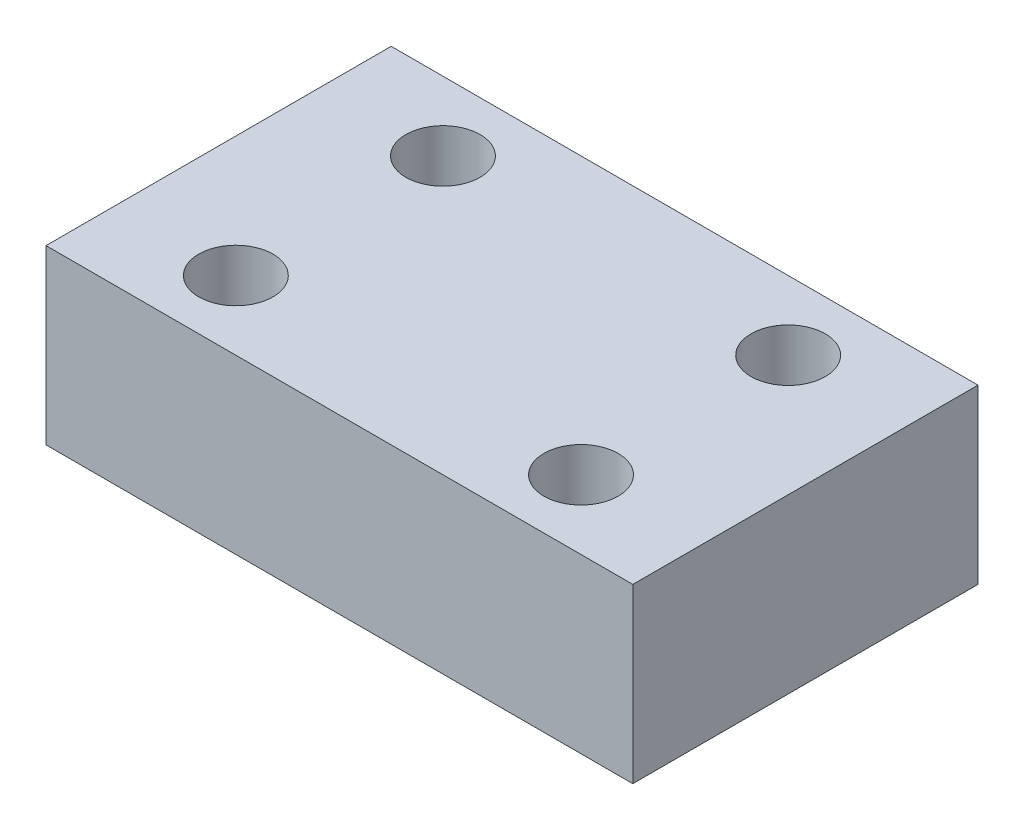
SolidWorks part; units mm, degrees
material "6061-T6 (SS)"
ref_plane "Front Plane" through (0, 0, 0) normal (0, 0, 1) x (1, 0, 0)
ref_plane "Top Plane" through (0, 0, 0) normal (0, 1, 0) x (1, 0, 0)
ref_plane "Right Plane" through (0, 0, 0) normal (1, 0, 0) x (0, 0, -1)
sketch "Sketch1" plane through (0, 0, 0) normal (0, 0, 1) x (1, 0, 0)
  line L0 (-70, 30) -> (-70, 10) construction
  line L1 (-80, 40) -> (80, 40)
  line L2 (-80, 40) -> (-80, 0)
  line L3 (-80, 0) -> (80, 0)
  line L4 (80, 40) -> (80, 0)
  line L9 (37, 23) -> (43, 23) construction
  line L10 (37, 23) -> (37, 17) construction
  line L11 (37, 17) -> (43, 17) construction
  line L12 (43, 23) -> (43, 17) construction
  line L13 (0, 0) -> (0, 40) construction
  line L14 (37, 20) -> (43, 20) construction
  line L15 (40, 17) -> (40, 23) construction
  line L16 (22.5, 40) -> (22.5, 22.95)
  line L17 (22.5, 40) -> (57.5, 40) construction
  line L18 (22.5, 40) -> (22.5, 23) construction
  line L19 (22.5, 23) -> (57.5, 23) construction
  line L20 (57.5, 40) -> (57.5, 23) construction
  line L21 (22.5, 22.95) -> (37, 22.95)
  line L22 (37, 22.95) -> (37, 17)
  line L23 (37, 17) -> (43, 17)
  line L24 (43, 17) -> (43, 22.95)
  line L25 (43, 22.95) -> (57.5, 22.95)
  line L26 (57.5, 22.95) -> (57.5, 40)
  circle A0 centre (-70, 30) radius 2.5 construction
  circle A1 centre (-70, 10) radius 2.5 construction
  circle A2 centre (70, 10) radius 2.5 construction
  circle A3 centre (70, 30) radius 2.5 construction
  point P10 (0, 0)
  point P15 (80, 20)
  point P31 (40, 23)
  dimension "D8" = 5
  dimension "D10" = 10
  dimension "D2" = 160
  dimension "D3" = 40
  dimension "D4" = 40
  dimension "D5" = 35
  dimension "D6" = 6
  dimension "D7" = 20
  dimension "D9" = 10
  dimension "D11" = 0.05
extrude "Boss-Extrude1" [suppressed] add sketch "Sketch1" against normal blind 20
sketch "Sketch4" [suppressed] plane through (0, 0, 0) normal (0, -1, 0) x (1, 0, 0)
  line L0 (-60, -10) -> (60, -10) construction
  line L2 (-80, 0) -> (80, 0)
  line L3 (-80, 0) -> (-80, -20)
  line L4 (-80, -20) -> (80, -20)
  line L5 (80, 0) -> (80, -20)
  circle A0 centre (0, -10) radius 2.5 construction
  circle A1 centre (60, -10) radius 2.5 construction
  circle A2 centre (-60, -10) radius 2.5 construction
  point P6 (0, -10)
  point P14 (80, -10)
  dimension "D1" = 5
  dimension "D2" = 120
sketch "Sketch8" [suppressed] plane through (0, 22.95, 0) normal (0, 1, 0) x (1, 0, 0)
  line L8 (37, 0) -> (22.5, 0) construction
  line L9 (22.5, 0) -> (22.5, 20) construction
  line L10 (22.5, 20) -> (37, 20) construction
  line L11 (37, 20) -> (37, 0) construction
  line L12 (57.5, 0) -> (43, 0) construction
  line L13 (43, 0) -> (43, 20) construction
  line L14 (43, 20) -> (57.5, 20) construction
  line L15 (57.5, 20) -> (57.5, 0) construction
  line L16 (30, 5) -> (50, 5) construction
  line L17 (37, 20) -> (43, 20)
  line L18 (37, 20) -> (37, 0) construction
  line L19 (37, 20) -> (37, 0) construction
  line L20 (30, 5) -> (30, 15) construction
  line L21 (30, 15) -> (50, 15) construction
  line L22 (50, 15) -> (50, 5) construction
  circle A0 centre (50, 5) radius 2 construction
  circle A1 centre (30, 5) radius 2 construction
  circle A2 centre (30, 15) radius 2 construction
  circle A3 centre (50, 15) radius 2 construction
  point P4 (40, 5)
  point P5 (40, 20)
  point P17 (50, 10)
  point P18 (43, 10)
  dimension "D1" = 4
  dimension "D2" = 20
  dimension "D3" = 10
hole_wizard "Tap Drill for M4x0.7 Tap1" [suppressed] positions "3DSketch3" profile "Sketch9" hole size "M4x0.7" standard "ANSI Metric"
sketch3d "3DSketch3" [suppressed]
  point P10 (30, 22.95, -5)
  point P12 (50, 22.95, -5)
  point P19 (30, 22.95, -15)
  point P21 (50, 22.95, -15)
sketch "Sketch9" plane through (30, 22.95, -5) normal (1, 0, 0) x (0, 0, 1)
  line L0 (0, 0) -> (0, 5.9914)
  line L1 (0, 5.9914) -> (1.65, 5)
  line L2 (1.65, 5) -> (1.65, 0)
  line L5 (1.65, 0) -> (0, 0)
  line L10 (0, 5.9914) -> (-1.65, 5) construction
  line L11 (0, -6.35) -> (0, 107.95) construction
  dimension "Hole Dia." = 3.3
  dimension "Hole Depth" = 5
  dimension "Drill Angle" = 118
hole_wizard "Tap Drill for M5x0.8 Tap3" [suppressed] positions "3DSketch4" profile "Sketch10" hole size "M5x0.8" standard "ANSI Metric"
sketch3d "3DSketch4" [suppressed]
  point P0 (-70, 30, 0)
  point P2 (-70, 10, 0)
  point P4 (70, 10, 0)
  point P6 (70, 30, 0)
sketch "Sketch10" plane through (-70, 30, 0) normal (1, 0, 0) x (0, -1, 0)
  line L0 (0, 0) -> (0, 20)
  line L1 (0, 20) -> (2.1, 20)
  line L2 (2.1, 20) -> (2.1, 0)
  line L5 (2.1, 0) -> (0, 0)
  line L11 (0, -6.35) -> (0, 107.95) construction
  dimension "Thru Hole Dia." = 4.2
  dimension "Thru Hole Depth" = 20
hole_wizard "Tap Drill for M5x0.8 Tap2" [suppressed] positions "3DSketch2" profile "Sketch5" hole size "M5x0.8" standard "ANSI Metric"
sketch3d "3DSketch2" [suppressed]
  point P0 (-60, 0, -10)
  point P2 (0, 0, -10)
  point P4 (60, 0, -10)
sketch "Sketch5" plane through (-60, 0, -10) normal (1, 0, 0) x (0, 0, -1)
  line L0 (0, 0) -> (0, 8.2618)
  line L1 (0, 8.2618) -> (2.1, 7)
  line L2 (2.1, 7) -> (2.1, 0)
  line L5 (2.1, 0) -> (0, 0)
  line L10 (0, 8.2618) -> (-2.1, 7) construction
  line L11 (0, -6.35) -> (0, 107.95) construction
  dimension "Hole Dia." = 4.2
  dimension "Hole Depth" = 7
  dimension "Drill Angle" = 118
fillet "Fillet1" [suppressed] radius 1
ref_plane "Plane1" [suppressed] through (0, 0, -10) normal (0, 0, -1) x (-1, 0, 0)
sketch "Sketch12" plane through (0, 0, 0) normal (0, 1, 0) x (1, 0, 0)
  line L1 (-17, 10) -> (17, 10)
  line L2 (-17, 10) -> (-17, -10)
  line L3 (-17, -10) -> (17, -10)
  line L4 (17, 10) -> (17, -10)
  line L5 (-10, 6) -> (10, 6) construction
  line L6 (-10, 6) -> (-10, -6) construction
  line L7 (-10, -6) -> (10, -6) construction
  line L8 (10, 6) -> (10, -6) construction
  circle A0 centre (-10, 6) radius 2 construction
  circle A1 centre (-10, -6) radius 2 construction
  circle A2 centre (10, -6) radius 2 construction
  circle A3 centre (10, 6) radius 2 construction
  point P8 (0, 6)
  point P9 (0, 10)
  point P11 (-10, 0)
  point P12 (-17, 0)
  dimension "D3" = 4
  dimension "D1" = 34
  dimension "D2" = 20
  dimension "D4" = 12
  dimension "D5" = 20
extrude "Boss-Extrude2" add sketch "Sketch12" against normal blind 10
hole_wizard "M4 Clearance Hole1" positions "3DSketch5" profile "Sketch13" hole size "M4" standard "ANSI Metric" end condition through all
sketch3d "3DSketch5"
  point P0 (-10, 0, -6)
  point P2 (-10, 0, 6)
  point P4 (10, 0, 6)
  point P7 (10, 0, -6)
sketch "Sketch13" plane through (-10, 0, -6) normal (1, 0, 0) x (0, 0, 1)
  line L0 (0, 0) -> (0, 10)
  line L1 (0, 10) -> (2.15, 10)
  line L2 (2.15, 10) -> (2.15, 0)
  line L5 (2.15, 0) -> (0, 0)
  line L11 (0, -6.35) -> (0, 107.95) construction
  dimension "Thru Hole Dia." = 4.3
  dimension "Thru Hole Depth" = 10
